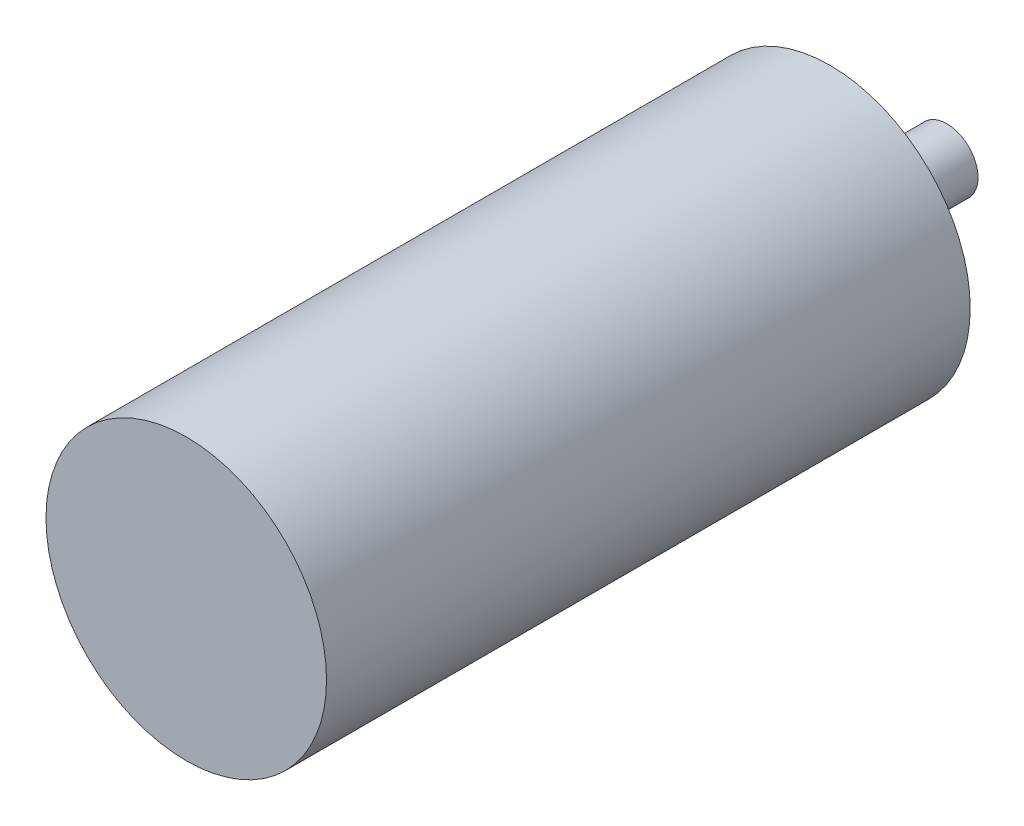
SolidWorks part; units mm, degrees
ref_plane "Front Plane" through (0, 0, 0) normal (0, 0, 1) x (1, 0, 0)
ref_plane "Top Plane" through (0, 0, 0) normal (0, 1, 0) x (1, 0, 0)
ref_plane "Right Plane" through (0, 0, 0) normal (1, 0, 0) x (0, 0, -1)
sketch "Sketch1" plane through (0, 0, 0) normal (0, 0, 1) x (1, 0, 0)
  circle A0 centre (0, 0) radius 18
  dimension "D1" = 36
extrude "Boss-Extrude1" add sketch "Sketch1" along normal blind 82.6
sketch "Sketch2" plane through (0, 0, 0) normal (0, 0, -1) x (-1, 0, 0)
  circle A0 centre (0, 0) radius 4
  dimension "D1" = 8
sketch "Sketch3" plane through (0, 0, 0) normal (0, 0, -1) x (-1, 0, 0)
  line L0 (0, 0) -> (0, 14) construction
  circle A0 centre (0, 14) radius 1.5
  circle A1 centre (14, 0) radius 1.5
  circle A2 centre (0, -14) radius 1.5
  circle A3 centre (-14, 0) radius 1.5
  point P2 (0, -1.0094)
  point P4 (6.7875, 0.7692)
  point P5 (0, 0)
  point P15 (5.4505, 0.8373)
  dimension "D1" = 3
  dimension "D2" = 14
  dimension "D4" = 14
  dimension "D3" = 4
extrude "Cut-Extrude1" cut sketch "Sketch3" against normal blind 5
extrude "Boss-Extrude3" add sketch "Sketch2" along normal blind 15
